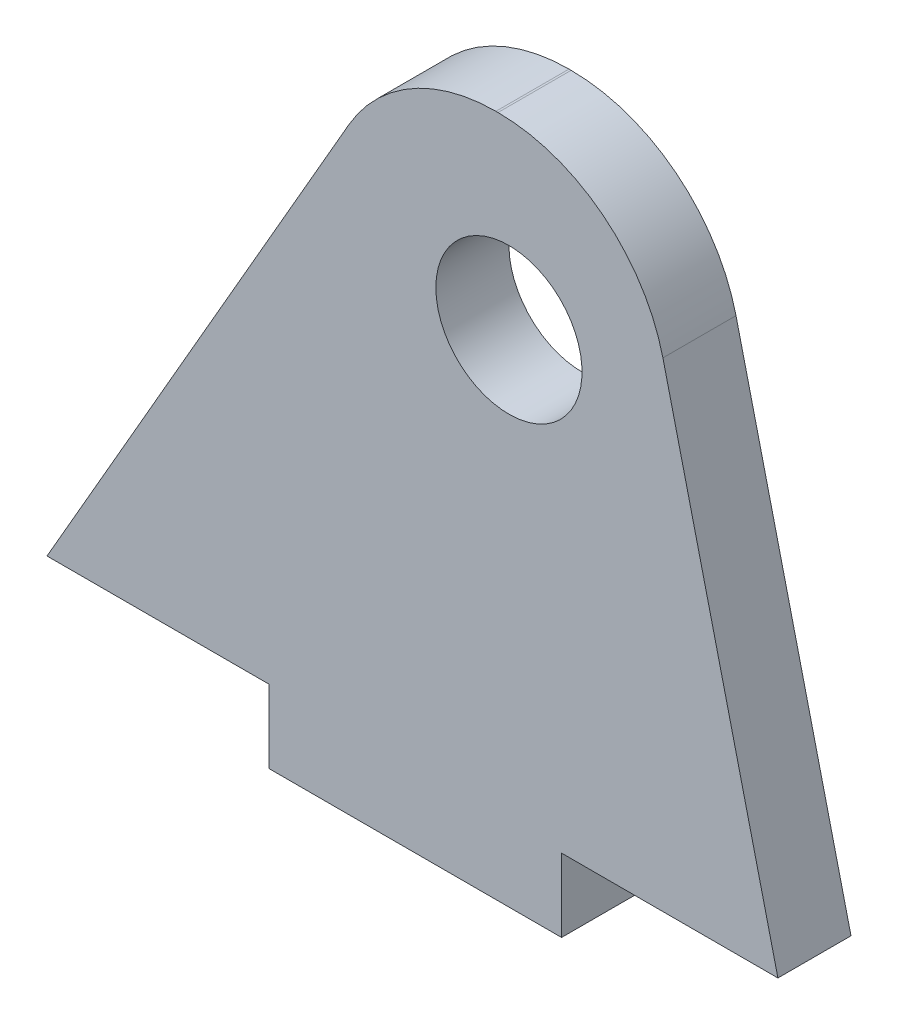
SolidWorks part; units mm, degrees
material "Custom Plastic"
ref_plane "X-Y Datum" through (0, 0, 0) normal (0, 0, 1) x (1, 0, 0)
ref_plane "X-Z Datum" through (0, 0, 0) normal (0, 1, 0) x (1, 0, 0)
ref_plane "Y-Z Datum" through (0, 0, 0) normal (1, 0, 0) x (0, 0, -1)
sketch "Sketch1" plane through (0, 0, 0) normal (0, 0, 1) x (1, 0, 0)
  line L0 (0, 0) -> (0, 50000) construction
  line L1 (0, 0) -> (50000, 0) construction
  line L2 (-62.1782, 0) -> (0, 0)
  line L3 (0, 0) -> (0, 55.1596)
  line L4 (0, 55.1596) -> (-62.1782, 55.1596)
  line L5 (-62.1782, 55.1596) -> (-62.1782, 0)
  dimension "D1" = 90
  dimension "D2" = 90
  dimension "D3" = 90
  dimension "D4" = 90
extrude "Boss-Extrude1" add sketch "Sketch1" along normal blind 3.175
hole_wizard "1/4 (0.25) Diameter Hole1" positions "Sketch2" profile "Sketch3" hole size "1/4" standard "ANSI Inch" end condition through all
sketch "Sketch2" plane through (0, 0, 0) normal (0, 0, -1) x (-1, 0, 0)
  line L0 (62.1782, 0) -> (0, 0) construction
  line L1 (62.1782, 55.1596) -> (62.1782, 0) construction
  point P0 (42.1122, 18.542)
  dimension "D1" = 18.542
  dimension "D2" = 20.066
sketch "Sketch3" plane through (-42.1122, 18.542, 0) normal (1, 0, 0) x (0, 1, 0)
  line L0 (0, 0) -> (0, 3.175)
  line L1 (0, 3.175) -> (3.175, 3.175)
  line L2 (3.175, 3.175) -> (3.175, 0)
  line L5 (3.175, 0) -> (0, 0)
  line L11 (0, -78.8889) -> (0, 107.95) construction
  dimension "Thru Hole Dia." = 6.35
  dimension "Thru Hole Depth" = 3.175
sketch "Sketch4" plane through (0, 0, 0) normal (0, 0, -1) x (-1, 0, 0)
  line L0 (62.1782, 0) -> (46.9382, 26.4795)
  line L1 (62.1782, 0) -> (0, 0) construction
  line L2 (46.9382, 26.4795) -> (36.7782, 26.4795)
  line L3 (36.7782, 26.4795) -> (30.4282, 0)
  line L4 (30.4282, 0) -> (62.1782, 0)
  line M6 (62.1782, 0) -> (62.1782, 55.1596)
  line M7 (62.1782, 55.1596) -> (0, 55.1596)
  line M8 (0, 55.1596) -> (0, 0)
  line M9 (0, 0) -> (62.1782, 0)
  dimension "D1" = 31.75
  dimension "D2" = 15.24
  dimension "D3" = 26.4795
  dimension "D4" = 10.16
extrude "Cut-Extrude6" cut sketch "Sketch4" against normal through all contours L3 L2 L0 M6 M7 M8 M9
fillet "Fillet1" radius 7.366 2 edges at (-46.9382, 26.4795, 1.5875) (-36.7782, 26.4795, 1.5875)
sketch "Sketch7" plane through (0, 0, 0) normal (0, 0, -1) x (-1, 0, 0)
  line L0 (39.8262, 0) -> (39.8262, -3.175)
  line L1 (62.1782, 0) -> (30.4282, 0) construction
  line L2 (39.8262, -3.175) -> (52.5262, -3.175)
  line L3 (52.5262, -3.175) -> (52.5262, 0)
  line L4 (52.5262, 0) -> (39.8262, 0)
  dimension "D1" = 3.175
  dimension "D2" = 12.7
  dimension "D3" = 9.652
extrude "Boss-Extrude2" add sketch "Sketch7" against normal blind 3.175
